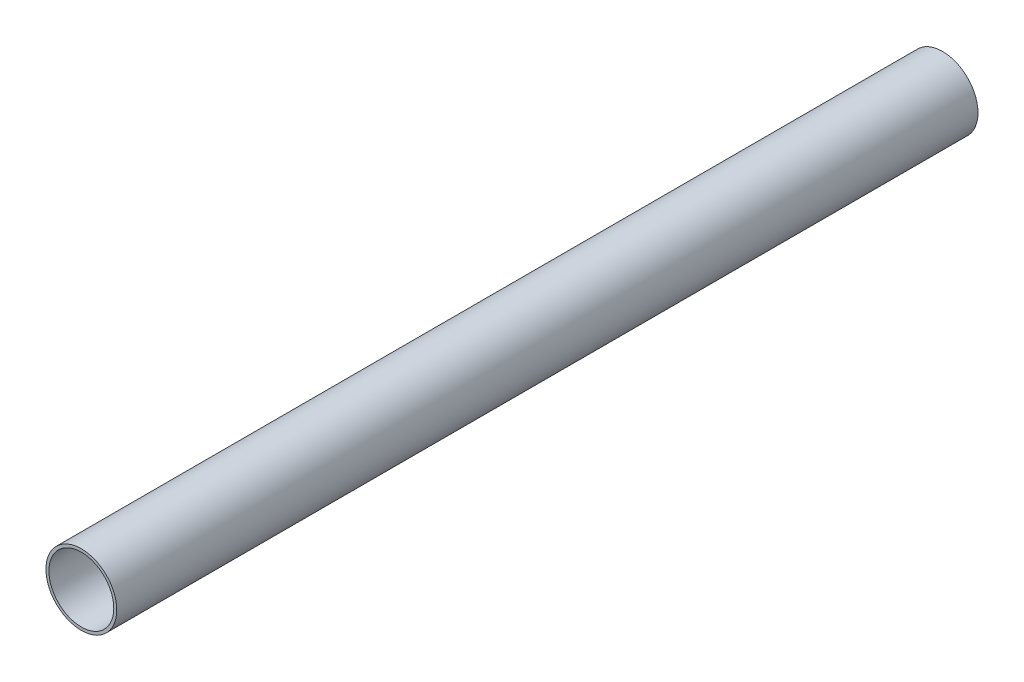
SolidWorks part; units mm, degrees
ref_plane "Front Plane" through (0, 0, 0) normal (0, 0, 1) x (1, 0, 0)
ref_plane "Top Plane" through (0, 0, 0) normal (0, 1, 0) x (1, 0, 0)
ref_plane "Right Plane" through (0, 0, 0) normal (1, 0, 0) x (0, 0, -1)
sketch "Motor Casing" plane through (0, 0, 0) normal (0, 0, 1) x (1, 0, 0)
  circle A1 centre (0, 0) radius 17.4625
  circle A5 centre (0, 0) radius 19.05
  dimension "D1" = 1.5875
extrude "Boss-Extrude1" add sketch "Motor Casing" along normal blind 463.55
